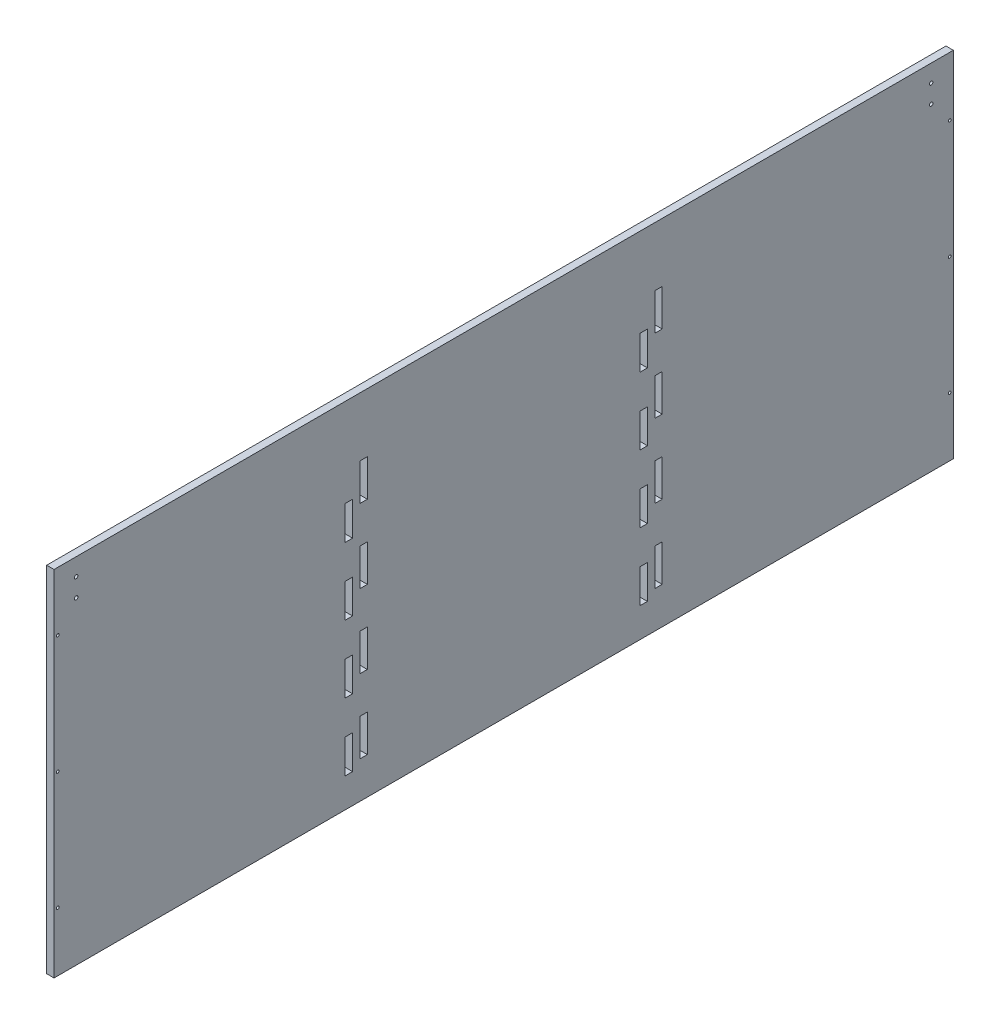
SolidWorks part; units mm, degrees
material "Acrylic (Medium-high impact)"
ref_plane "Front Plane" through (0, 0, 0) normal (0, 0, 1) x (1, 0, 0)
ref_plane "Top Plane" through (0, 0, 0) normal (0, 1, 0) x (1, 0, 0)
ref_plane "Right Plane" through (0, 0, 0) normal (1, 0, 0) x (0, 0, -1)
sketch "Sketch1" plane through (0, 0, 0) normal (1, 0, 0) x (0, 0, -1)
  line L0 (0, 152.4) -> (0, -152.4) construction
  line L1 (-381, 152.4) -> (381, 152.4)
  line L2 (-381, 152.4) -> (-381, -152.4)
  line L3 (-381, -152.4) -> (381, -152.4)
  line L4 (381, 152.4) -> (381, -152.4)
  line L5 (-381, 107.95) -> (-381, 63.5)
  line L10 (-381, 152.4) -> (-387.35, 152.4)
  line L11 (-381, 152.4) -> (-381, 107.95)
  line L12 (-381, 107.95) -> (-387.35, 107.95)
  line L13 (-387.35, 152.4) -> (-387.35, 107.95)
  line L14 (381, 152.4) -> (387.35, 152.4)
  line L15 (381, 152.4) -> (381, 107.95)
  line L16 (381, 107.95) -> (387.35, 107.95)
  line L17 (387.35, 152.4) -> (387.35, 107.95)
  line L18 (-387.35, -152.4) -> (-327.7577, -152.4)
  line L19 (-387.35, -152.4) -> (-387.35, -158.75)
  line L20 (-387.35, -158.75) -> (-327.7577, -158.75)
  line L21 (-327.7577, -152.4) -> (-327.7577, -158.75)
  line L22 (-381, 107.95) -> (-387.35, 107.95)
  line L23 (-387.35, 107.95) -> (-387.35, 63.5)
  line L24 (-381, 63.5) -> (-387.35, 63.5)
  line L25 (381, 107.95) -> (381, 63.5)
  line L26 (381, 107.95) -> (387.35, 107.95)
  line L27 (387.35, 107.95) -> (387.35, 63.5)
  line L28 (381, 63.5) -> (387.35, 63.5)
  line L29 (-381, 63.5) -> (-381, 19.05)
  line L30 (-381, 63.5) -> (-387.35, 63.5)
  line L31 (-387.35, 63.5) -> (-387.35, 19.05)
  line L32 (-381, 19.05) -> (-387.35, 19.05)
  line L33 (381, 63.5) -> (381, 19.05)
  line L34 (381, 63.5) -> (387.35, 63.5)
  line L35 (387.35, 63.5) -> (387.35, 19.05)
  line L36 (381, 19.05) -> (387.35, 19.05)
  line L37 (-381, 19.05) -> (-381, -25.4)
  line L38 (-381, 19.05) -> (-387.35, 19.05)
  line L39 (-387.35, 19.05) -> (-387.35, -25.4)
  line L40 (-381, -25.4) -> (-387.35, -25.4)
  line L41 (381, 19.05) -> (381, -25.4)
  line L42 (381, 19.05) -> (387.35, 19.05)
  line L43 (387.35, 19.05) -> (387.35, -25.4)
  line L44 (381, -25.4) -> (387.35, -25.4)
  line L45 (-381, -25.4) -> (-381, -69.85)
  line L46 (-381, -25.4) -> (-387.35, -25.4)
  line L47 (-387.35, -25.4) -> (-387.35, -69.85)
  line L48 (-381, -69.85) -> (-387.35, -69.85)
  line L49 (381, -25.4) -> (381, -69.85)
  line L50 (381, -25.4) -> (387.35, -25.4)
  line L51 (387.35, -25.4) -> (387.35, -69.85)
  line L52 (381, -69.85) -> (387.35, -69.85)
  line L53 (-381, -69.85) -> (-381, -114.3)
  line L54 (-381, -69.85) -> (-387.35, -69.85)
  line L55 (-387.35, -69.85) -> (-387.35, -114.3)
  line L56 (-381, -114.3) -> (-387.35, -114.3)
  line L57 (381, -69.85) -> (381, -114.3)
  line L58 (381, -69.85) -> (387.35, -69.85)
  line L59 (387.35, -69.85) -> (387.35, -114.3)
  line L60 (381, -114.3) -> (387.35, -114.3)
  line L61 (-381, -114.3) -> (-381, -158.75)
  line L62 (-381, -114.3) -> (-387.35, -114.3)
  line L63 (-387.35, -114.3) -> (-387.35, -158.75)
  line L64 (-381, -158.75) -> (-387.35, -158.75)
  line L65 (381, -114.3) -> (381, -158.75)
  line L66 (381, -114.3) -> (387.35, -114.3)
  line L67 (387.35, -114.3) -> (387.35, -158.75)
  line L68 (381, -158.75) -> (387.35, -158.75)
  line L69 (-327.7577, -158.75) -> (-268.1654, -158.75)
  line L70 (-327.7577, -152.4) -> (-327.7577, -158.75)
  line L71 (-327.7577, -152.4) -> (-268.1654, -152.4)
  line L72 (-268.1654, -152.4) -> (-268.1654, -158.75)
  line L73 (-268.1654, -158.75) -> (-208.5731, -158.75)
  line L74 (-268.1654, -152.4) -> (-268.1654, -158.75)
  line L75 (-268.1654, -152.4) -> (-208.5731, -152.4)
  line L76 (-208.5731, -152.4) -> (-208.5731, -158.75)
  line L77 (-208.5731, -158.75) -> (-148.9808, -158.75)
  line L78 (-208.5731, -152.4) -> (-208.5731, -158.75)
  line L79 (-208.5731, -152.4) -> (-148.9808, -152.4)
  line L80 (-148.9808, -152.4) -> (-148.9808, -158.75)
  line L81 (-148.9808, -158.75) -> (-89.3885, -158.75)
  line L82 (-148.9808, -152.4) -> (-148.9808, -158.75)
  line L83 (-148.9808, -152.4) -> (-89.3885, -152.4)
  line L84 (-89.3885, -152.4) -> (-89.3885, -158.75)
  line L85 (-89.3885, -158.75) -> (-29.7962, -158.75)
  line L86 (-89.3885, -152.4) -> (-89.3885, -158.75)
  line L87 (-89.3885, -152.4) -> (-29.7962, -152.4)
  line L88 (-29.7962, -152.4) -> (-29.7962, -158.75)
  line L89 (-29.7962, -158.75) -> (29.7962, -158.75)
  line L90 (-29.7962, -152.4) -> (-29.7962, -158.75)
  line L91 (-29.7962, -152.4) -> (29.7962, -152.4)
  line L92 (29.7962, -152.4) -> (29.7962, -158.75)
  line L93 (29.7962, -158.75) -> (89.3885, -158.75)
  line L94 (29.7962, -152.4) -> (29.7962, -158.75)
  line L95 (29.7962, -152.4) -> (89.3885, -152.4)
  line L96 (89.3885, -152.4) -> (89.3885, -158.75)
  line L97 (89.3885, -158.75) -> (148.9808, -158.75)
  line L98 (89.3885, -152.4) -> (89.3885, -158.75)
  line L99 (89.3885, -152.4) -> (148.9808, -152.4)
  line L100 (148.9808, -152.4) -> (148.9808, -158.75)
  line L101 (148.9808, -158.75) -> (208.5731, -158.75)
  line L102 (148.9808, -152.4) -> (148.9808, -158.75)
  line L103 (148.9808, -152.4) -> (208.5731, -152.4)
  line L104 (208.5731, -152.4) -> (208.5731, -158.75)
  line L105 (208.5731, -158.75) -> (268.1654, -158.75)
  line L106 (208.5731, -152.4) -> (208.5731, -158.75)
  line L107 (208.5731, -152.4) -> (268.1654, -152.4)
  line L108 (268.1654, -152.4) -> (268.1654, -158.75)
  line L125 (-123.825, 0) -> (123.825, 0) construction
  line L126 (-130.175, 41.956) -> (-123.825, 41.956) construction
  line L127 (-130.175, 41.956) -> (-130.175, -41.956) construction
  line L128 (-130.175, -41.956) -> (-123.825, -41.956) construction
  line L129 (-123.825, 41.956) -> (-123.825, -41.956) construction
  line L138 (123.825, 41.956) -> (130.175, 41.956) construction
  line L139 (123.825, 41.956) -> (123.825, -41.956) construction
  line L140 (123.825, -41.956) -> (130.175, -41.956) construction
  line L141 (130.175, 41.956) -> (130.175, -41.956) construction
  line L143 (268.1654, -158.75) -> (327.7577, -158.75)
  line L144 (268.1654, -152.4) -> (268.1654, -158.75)
  line L145 (268.1654, -152.4) -> (327.7577, -152.4)
  line L146 (327.7577, -152.4) -> (327.7577, -158.75)
  line L147 (327.7577, -158.75) -> (387.35, -158.75)
  line L148 (327.7577, -152.4) -> (327.7577, -158.75)
  line L149 (327.7577, -152.4) -> (387.35, -152.4)
  line L150 (387.35, -152.4) -> (387.35, -158.75)
  point P6 (0, 0)
  point P113 (-127, 41.956)
  point P114 (127, 41.956)
  point P117 (0, 0)
  dimension "D1" = 762
  dimension "D2" = 304.8
  dimension "D3" = 774.7
  dimension "D4" = 311.15
  dimension "D5" = 44.45
  dimension "D7" = 59.5923
  dimension "D9" = 254
  dimension "D10" = 6.35
  dimension "D6" = 7
  dimension "D8" = 13
extrude "Boss-Extrude1" add sketch "Sketch1" along normal blind 6.35
sketch "Sketch3" plane through (6.35, 0, 0) normal (1, 0, 0) x (0, 0, -1)
  line L0 (-130.1762, -127) -> (-130.1762, 76.2) construction
  line L5 (-136.5262, 76.2) -> (-130.1762, 76.2)
  line L6 (-136.5262, 76.2) -> (-136.5262, 47.1714)
  line L7 (-136.5262, 47.1714) -> (-130.1762, 47.1714)
  line L8 (-130.1762, 76.2) -> (-130.1762, 47.1714)
  line L9 (-117.4738, 101.6) -> (-123.8238, 101.6)
  line L10 (-117.4738, 101.6) -> (-117.4738, 69.85)
  line L11 (-117.4738, 69.85) -> (-123.8238, 69.85)
  line L12 (-123.8238, 101.6) -> (-123.8238, 69.85)
  line L13 (-381, -152.4) -> (381, -152.4) construction
  line L14 (-123.8238, -152.4) -> (-123.8238, 101.6) construction
  line L15 (-130.1762, 76.2) -> (-123.8238, 76.2) construction
  line L16 (-127, 41.956) -> (-127, 76.2) construction
  line L17 (-130.175, 41.956) -> (-123.825, 41.956) construction
  line L18 (-117.4738, 69.85) -> (-117.4738, 38.1)
  line L19 (-117.4738, 69.85) -> (-123.8238, 69.85)
  line L20 (-123.8238, 69.85) -> (-123.8238, 38.1)
  line L21 (-117.4738, 38.1) -> (-123.8238, 38.1)
  line L22 (-117.4738, 38.1) -> (-117.4738, 6.35)
  line L23 (-117.4738, 38.1) -> (-123.8238, 38.1)
  line L24 (-123.8238, 38.1) -> (-123.8238, 6.35)
  line L25 (-117.4738, 6.35) -> (-123.8238, 6.35)
  line L26 (-117.4738, 6.35) -> (-117.4738, -25.4)
  line L27 (-117.4738, 6.35) -> (-123.8238, 6.35)
  line L28 (-123.8238, 6.35) -> (-123.8238, -25.4)
  line L29 (-117.4738, -25.4) -> (-123.8238, -25.4)
  line L30 (-117.4738, -25.4) -> (-117.4738, -57.15)
  line L31 (-117.4738, -25.4) -> (-123.8238, -25.4)
  line L32 (-123.8238, -25.4) -> (-123.8238, -57.15)
  line L33 (-117.4738, -57.15) -> (-123.8238, -57.15)
  line L34 (-117.4738, -57.15) -> (-117.4738, -88.9)
  line L35 (-117.4738, -57.15) -> (-123.8238, -57.15)
  line L36 (-123.8238, -57.15) -> (-123.8238, -88.9)
  line L37 (-117.4738, -88.9) -> (-123.8238, -88.9)
  line L38 (-117.4738, -88.9) -> (-117.4738, -120.65)
  line L39 (-117.4738, -88.9) -> (-123.8238, -88.9)
  line L40 (-123.8238, -88.9) -> (-123.8238, -120.65)
  line L41 (-117.4738, -120.65) -> (-123.8238, -120.65)
  line L42 (-136.5262, 47.1714) -> (-136.5262, 18.1429)
  line L43 (-136.5262, 47.1714) -> (-130.1762, 47.1714)
  line L44 (-130.1762, 47.1714) -> (-130.1762, 18.1429)
  line L45 (-136.5262, 18.1429) -> (-130.1762, 18.1429)
  line L46 (-136.5262, 18.1429) -> (-136.5262, -10.8857)
  line L47 (-136.5262, 18.1429) -> (-130.1762, 18.1429)
  line L48 (-130.1762, 18.1429) -> (-130.1762, -10.8857)
  line L49 (-136.5262, -10.8857) -> (-130.1762, -10.8857)
  line L50 (-136.5262, -10.8857) -> (-136.5262, -39.9143)
  line L51 (-136.5262, -10.8857) -> (-130.1762, -10.8857)
  line L52 (-130.1762, -10.8857) -> (-130.1762, -39.9143)
  line L53 (-136.5262, -39.9143) -> (-130.1762, -39.9143)
  line L54 (-136.5262, -39.9143) -> (-136.5262, -68.9429)
  line L55 (-136.5262, -39.9143) -> (-130.1762, -39.9143)
  line L56 (-130.1762, -39.9143) -> (-130.1762, -68.9429)
  line L57 (-136.5262, -68.9429) -> (-130.1762, -68.9429)
  line L58 (-136.5262, -68.9429) -> (-136.5262, -97.9714)
  line L59 (-136.5262, -68.9429) -> (-130.1762, -68.9429)
  line L60 (-130.1762, -68.9429) -> (-130.1762, -97.9714)
  line L61 (-136.5262, -97.9714) -> (-130.1762, -97.9714)
  line L62 (-136.5262, -97.9714) -> (-136.5262, -127)
  line L63 (-136.5262, -97.9714) -> (-130.1762, -97.9714)
  line L64 (-130.1762, -97.9714) -> (-130.1762, -127)
  line L65 (-136.5262, -127) -> (-130.1762, -127)
  line L66 (-117.4738, -120.65) -> (-117.4738, -152.4)
  line L67 (-117.4738, -120.65) -> (-123.8238, -120.65)
  line L68 (-123.8238, -120.65) -> (-123.8238, -152.4)
  line L69 (-117.4738, -152.4) -> (-123.8238, -152.4)
  line L70 (117.4738, 76.2) -> (123.8238, 76.2)
  line L71 (117.4738, 76.2) -> (117.4738, 47.1714)
  line L72 (117.4738, 47.1714) -> (123.8238, 47.1714)
  line L73 (123.8238, 76.2) -> (123.8238, 47.1714)
  line L74 (136.5262, 101.6) -> (130.1762, 101.6)
  line L75 (136.5262, 101.6) -> (136.5262, 69.85)
  line L76 (136.5262, 69.85) -> (130.1762, 69.85)
  line L77 (130.1762, 101.6) -> (130.1762, 69.85)
  line L78 (136.5262, 69.85) -> (136.5262, 38.1)
  line L79 (136.5262, 69.85) -> (130.1762, 69.85)
  line L80 (130.1762, 69.85) -> (130.1762, 38.1)
  line L81 (136.5262, 38.1) -> (130.1762, 38.1)
  line L82 (136.5262, 38.1) -> (136.5262, 6.35)
  line L83 (136.5262, 38.1) -> (130.1762, 38.1)
  line L84 (130.1762, 38.1) -> (130.1762, 6.35)
  line L85 (136.5262, 6.35) -> (130.1762, 6.35)
  line L86 (136.5262, 6.35) -> (136.5262, -25.4)
  line L87 (136.5262, 6.35) -> (130.1762, 6.35)
  line L88 (130.1762, 6.35) -> (130.1762, -25.4)
  line L89 (136.5262, -25.4) -> (130.1762, -25.4)
  line L90 (136.5262, -25.4) -> (136.5262, -57.15)
  line L91 (136.5262, -25.4) -> (130.1762, -25.4)
  line L92 (130.1762, -25.4) -> (130.1762, -57.15)
  line L93 (136.5262, -57.15) -> (130.1762, -57.15)
  line L94 (136.5262, -57.15) -> (136.5262, -88.9)
  line L95 (136.5262, -57.15) -> (130.1762, -57.15)
  line L96 (130.1762, -57.15) -> (130.1762, -88.9)
  line L97 (136.5262, -88.9) -> (130.1762, -88.9)
  line L98 (136.5262, -88.9) -> (136.5262, -120.65)
  line L99 (136.5262, -88.9) -> (130.1762, -88.9)
  line L100 (130.1762, -88.9) -> (130.1762, -120.65)
  line L101 (136.5262, -120.65) -> (130.1762, -120.65)
  line L102 (117.4738, 47.1714) -> (117.4738, 18.1429)
  line L103 (117.4738, 47.1714) -> (123.8238, 47.1714)
  line L104 (123.8238, 47.1714) -> (123.8238, 18.1429)
  line L105 (117.4738, 18.1429) -> (123.8238, 18.1429)
  line L106 (117.4738, 18.1429) -> (117.4738, -10.8857)
  line L107 (117.4738, 18.1429) -> (123.8238, 18.1429)
  line L108 (123.8238, 18.1429) -> (123.8238, -10.8857)
  line L109 (117.4738, -10.8857) -> (123.8238, -10.8857)
  line L110 (117.4738, -10.8857) -> (117.4738, -39.9143)
  line L111 (117.4738, -10.8857) -> (123.8238, -10.8857)
  line L112 (123.8238, -10.8857) -> (123.8238, -39.9143)
  line L113 (117.4738, -39.9143) -> (123.8238, -39.9143)
  line L114 (117.4738, -39.9143) -> (117.4738, -68.9429)
  line L115 (117.4738, -39.9143) -> (123.8238, -39.9143)
  line L116 (123.8238, -39.9143) -> (123.8238, -68.9429)
  line L117 (117.4738, -68.9429) -> (123.8238, -68.9429)
  line L118 (117.4738, -68.9429) -> (117.4738, -97.9714)
  line L119 (117.4738, -68.9429) -> (123.8238, -68.9429)
  line L120 (123.8238, -68.9429) -> (123.8238, -97.9714)
  line L121 (117.4738, -97.9714) -> (123.8238, -97.9714)
  line L122 (117.4738, -97.9714) -> (117.4738, -127)
  line L123 (117.4738, -97.9714) -> (123.8238, -97.9714)
  line L124 (123.8238, -97.9714) -> (123.8238, -127)
  line L125 (117.4738, -127) -> (123.8238, -127)
  line L126 (136.5262, -120.65) -> (136.5262, -152.4)
  line L127 (136.5262, -120.65) -> (130.1762, -120.65)
  line L128 (130.1762, -120.65) -> (130.1762, -152.4)
  line L129 (136.5262, -152.4) -> (130.1762, -152.4)
  line L130 (123.8238, -127) -> (123.8238, 76.2) construction
  line L131 (130.1762, -152.4) -> (130.1762, 101.6) construction
  line L132 (123.8238, 76.2) -> (130.1762, 76.2) construction
  line L133 (127, 41.956) -> (127, 76.2) construction
  line L134 (123.825, 41.956) -> (130.175, 41.956) construction
  dimension "D1" = 203.2
  dimension "D2" = 254
  dimension "D3" = 25.4
  dimension "D4" = 6.3525
  dimension "D5" = 6.35
  dimension "D7" = 31.75
  dimension "D9" = 29.0286
  dimension "D6" = 8
  dimension "D8" = 7
  dimension "D10" = 2
extrude "Cut-Extrude1" cut sketch "Sketch3" against normal through all contours L41 L38 L37 L40 | L33 L30 L29 L32 | L25 L22 L21 L24 | L9 L12 L11 L10 | L8 L5 L6 L7 | L46 L49 L48 L45 | L54 L57 L56 L53 | L62 L65 L64 L61 | L74 L77 L76 L75 | L73 L70 L71 L72 | L85 L82 L81 L84 | L106 L109 L108 L105 | L93 L90 L89 L92 | L114 L117 L116 L113 | L101 L98 L97 L100 | L122 L125 L124 L121
sketch "Sketch4" plane through (6.35, 0, 0) normal (1, 0, 0) x (0, 0, -1)
  line L0 (0, 152.4) -> (0, -152.4) construction
  line L1 (-387.35, 152.4) -> (387.35, 152.4) construction
  line L5 (-387.35, 152.4) -> (-387.35, 107.95) construction
  circle A0 centre (-368.3, 137.4) radius 1.5
  circle A1 centre (-368.3, 121.65) radius 1.5
  circle A2 centre (368.3, 137.4) radius 1.5
  circle A3 centre (368.3, 121.65) radius 1.5
  dimension "D1" = 3
  dimension "D2" = 3
  dimension "D3" = 19.05
  dimension "D4" = 15.75
  dimension "D5" = 15
extrude "Cut-Extrude2" cut sketch "Sketch4" against normal up to surface (6.35 mm away) up to face at (0, 3.6286, 133.3512)
sketch "Sketch5" plane through (6.35, 0, 0) normal (1, 0, 0) x (0, 0, -1)
  line L0 (-387.35, 63.5) -> (-381, 63.5)
  line L1 (-381, 63.5) -> (-381, 19.05)
  line L2 (-381, 19.05) -> (-387.35, 19.05)
  line L3 (-387.35, 19.05) -> (-387.35, 63.5)
  line L4 (-387.35, -25.4) -> (-381, -25.4)
  line L5 (-381, -25.4) -> (-381, -69.85)
  line L6 (-381, -69.85) -> (-387.35, -69.85)
  line L7 (-387.35, -69.85) -> (-387.35, -25.4)
  line L9 (-208.5731, -152.4) -> (-148.9808, -152.4)
  line L10 (-208.5731, -152.4) -> (-208.5731, -158.75)
  line L11 (-208.5731, -158.75) -> (-148.9808, -158.75)
  line L12 (-148.9808, -152.4) -> (-148.9808, -158.75)
  line L13 (-89.3885, -152.4) -> (-29.7962, -152.4)
  line L14 (-89.3885, -152.4) -> (-89.3885, -158.75)
  line L15 (-89.3885, -158.75) -> (-29.7962, -158.75)
  line L16 (-29.7962, -152.4) -> (-29.7962, -158.75)
  line L17 (29.7962, -152.4) -> (89.3885, -152.4)
  line L18 (29.7962, -152.4) -> (29.7962, -158.75)
  line L19 (29.7962, -158.75) -> (89.3885, -158.75)
  line L20 (89.3885, -152.4) -> (89.3885, -158.75)
  line L21 (148.9808, -152.4) -> (208.5731, -152.4)
  line L22 (148.9808, -152.4) -> (148.9808, -158.75)
  line L23 (148.9808, -158.75) -> (208.5731, -158.75)
  line L24 (208.5731, -152.4) -> (208.5731, -158.75)
  line L25 (387.35, -69.85) -> (381, -69.85)
  line L26 (387.35, -69.85) -> (387.35, -25.4)
  line L27 (387.35, -25.4) -> (381, -25.4)
  line L28 (381, -69.85) -> (381, -25.4)
  line L29 (387.35, 19.05) -> (381, 19.05)
  line L30 (387.35, 19.05) -> (387.35, 63.5)
  line L31 (387.35, 63.5) -> (381, 63.5)
  line L32 (381, 19.05) -> (381, 63.5)
extrude "Cut-Extrude3" cut sketch "Sketch5" against normal up to surface (6.35 mm away) up to face at (0, 121.65, 366.8)
sketch "Sketch6" plane through (6.35, 0, 0) normal (1, 0, 0) x (0, 0, -1)
  line L0 (-387.35, 107.95) -> (-387.35, -114.3)
  line L1 (-387.35, -114.3) -> (-381, -114.3)
  line L2 (-381, -114.3) -> (-381, 107.95)
  line L3 (-381, 107.95) -> (-387.35, 107.95)
  line L16 (387.35, 107.95) -> (387.35, -114.3)
  line L17 (387.35, -114.3) -> (381, -114.3)
  line L18 (381, -114.3) -> (381, 107.95)
  line L19 (381, 107.95) -> (387.35, 107.95)
extrude "Boss-Extrude2" add sketch "Sketch6" against normal up to surface (6.35 mm away) up to face at (0, 121.65, 366.8)
sketch "Sketch7" plane through (6.35, 0, 0) normal (1, 0, 0) x (0, 0, -1)
  line L1 (-387.35, -152.4) -> (387.35, -152.4)
  line L2 (-387.35, -152.4) -> (-387.35, -167.0965)
  line L3 (-387.35, -167.0965) -> (387.35, -167.0965)
  line L4 (387.35, -152.4) -> (387.35, -167.0965)
extrude "Cut-Extrude4" cut sketch "Sketch7" against normal up to surface (6.35 mm away) up to face at (0, -103.7167, 0)
sketch "Sketch8" plane through (6.35, 0, 0) normal (1, 0, 0) x (0, 0, -1)
  line L0 (381, 177.2054) -> (381, -220.8562) construction
  line L1 (387.35, 152.4) -> (387.35, -152.4) construction
  line L2 (0, 194.1353) -> (0, -231.8067) construction
  line L3 (-387.35, 152.4) -> (-387.35, -152.4) construction
  line L4 (-387.35, 152.4) -> (387.35, 152.4) construction
  line L5 (-381, 177.2054) -> (-381, -220.8562) construction
  circle A1 centre (384.175, 101.6) radius 1.1906
  circle A2 centre (384.175, 0) radius 1.1906
  circle A4 centre (384.175, -101.6) radius 1.1906
  circle A5 centre (-384.175, -101.6) radius 1.1906
  circle A6 centre (-384.175, 0) radius 1.1906
  circle A7 centre (-384.175, 101.6) radius 1.1906
  dimension "D3" = 50.8
  dimension "D6" = 3.175
  dimension "D1" = 6.35
  dimension "D2" = 387.35
  dimension "D4" = 101.6
  dimension "D5" = 101.6
  dimension "D7" = 3.175
  dimension "D8" = 3.175
extrude "Holes for plastic screws" cut sketch "Sketch8" against normal blind 10
equation "\"Height\"= 12in"
equation "\"Depth\"= 7in"
equation "\"WallThickness\"= 0.25in"
equation "\"FloorThickness\"= 0.25in"
equation "\"D2@Sketch1\"=\"Height\""
equation "\"D3@Sketch1\"=\"D1@Sketch1\"+2*\"WallThickness\""
equation "\"D4@Sketch1\"=\"D2@Sketch1\"+\"FloorThickness\""
equation "\"D5@Sketch1\"=\"D4@Sketch1\"/7"
equation "\"D7@Sketch1\"=\"D3@Sketch1\"/\"D8@Sketch1\""
equation "\"D1@Boss-Extrude1\"=\"WallThickness\""
equation "\"Width\" = 30in"
equation "\"D4@Sketch3\"=\"WallThickness\"+(1/16in)"
equation "\"D5@Sketch3\"=\"WallThickness\""
equation "\"D7@Sketch3\"=\"D2@Sketch3\"/\"D6@Sketch3\""
equation "\"D9@Sketch3\"=\"D1@Sketch3\"/\"D8@Sketch3\""
equation "\"D10@Sketch1\"=\"WallThickness\""
equation "\"D1@Sketch1\"=\"Width\""
